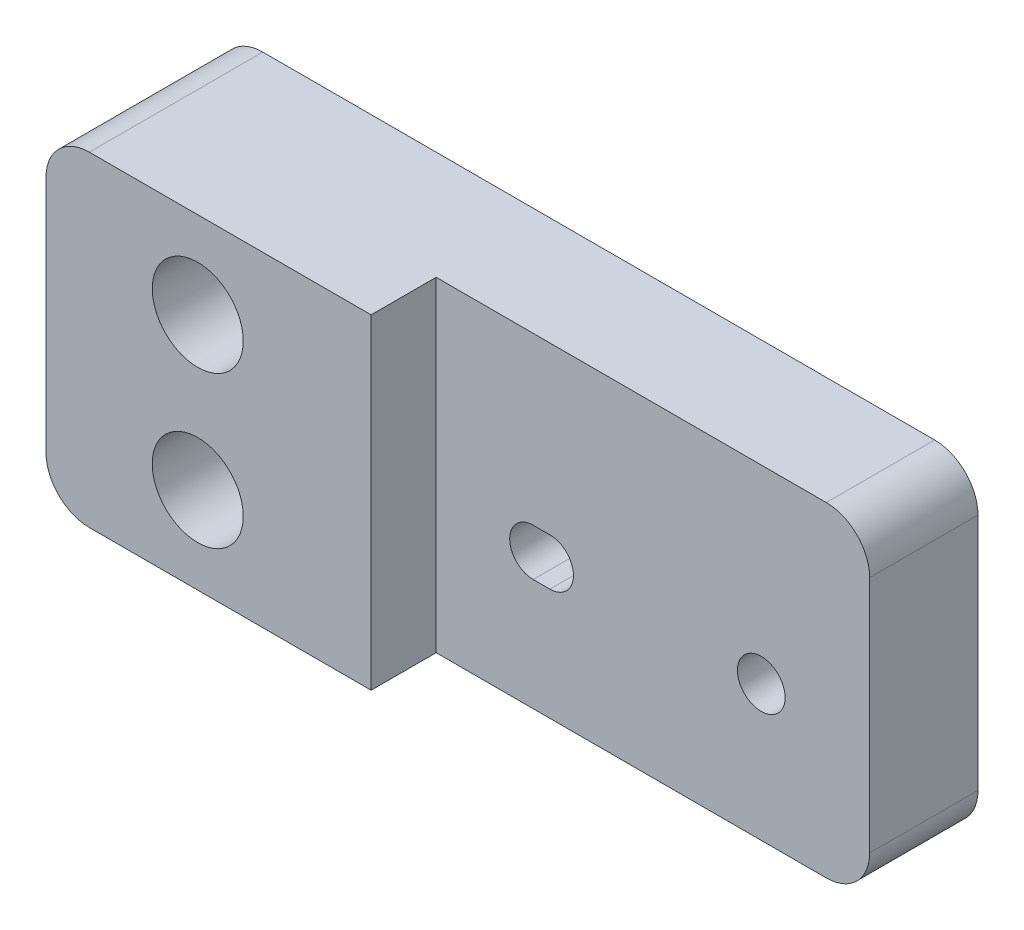
SolidWorks part; units mm, degrees
ref_plane "Plan de face" through (0, 0, 0) normal (0, 0, 1) x (1, 0, 0)
ref_plane "Plan de dessus" through (0, 0, 0) normal (0, 1, 0) x (1, 0, 0)
ref_plane "Plan de droite" through (0, 0, 0) normal (1, 0, 0) x (0, 0, -1)
sketch "Esquisse2" plane through (0, 0, 0) normal (0, 0, 1) x (1, 0, 0)
  line L0 (9.1879, 0.75) -> (5, 0.75) construction
  line L1 (18, 0.75) -> (-13, 0.75)
  line L2 (20, -1.25) -> (20, -12.25)
  line L3 (18, -14.25) -> (-13, -14.25)
  line L4 (-15, -1.25) -> (-15, -12.25)
  line L5 (20, -0.3) -> (20, -9.7) construction
  arc A0 (18, 0.75) -> (20, -1.25) centre (18, -1.25) cw
  arc A1 (20, -12.25) -> (18, -14.25) centre (18, -12.25) cw
  arc A2 (-13, 0.75) -> (-15, -1.25) centre (-13, -1.25) ccw
  arc A3 (-13, -14.25) -> (-15, -12.25) centre (-13, -12.25) cw
  circle A4 centre (-8, -10.25) radius 2.1
  circle A5 centre (-8, -3.25) radius 2.1
  point P12 (20, -14.25)
  point P15 (-15, 0.75)
  point P18 (-15, -14.25)
  dimension "D3" = 2
  dimension "D4" = 4.2
  dimension "D5" = 7
  dimension "D6" = 11
  dimension "D7" = 4.2
  dimension "D8" = 7
  dimension "D9" = 4
  dimension "D1" = 15
  dimension "D2" = 35
extrude "Boss.-Extru.1" add sketch "Esquisse2" along normal blind 5 contours A3 L3 A1 L2 A0 L1 A2 L4 | A4 | A5
sketch "Esquisse4" plane through (0, 0, 5) normal (0, 0, 1) x (1, 0, 0)
  line L0 (0, 0.75) -> (0, -14.25)
  line L4 (-15, -1.25) -> (-15, -12.25)
  line L5 (-13, -14.25) -> (18, -14.25)
  line L6 (20, -12.25) -> (20, -1.25)
  line L7 (18, 0.75) -> (-13, 0.75)
  line L8 (-15, -1.25) -> (-15, -12.25)
  line L9 (-13, -14.25) -> (0, -14.25)
  line L11 (0, 0.75) -> (-13, 0.75)
  circle A0 centre (-8, -10.25) radius 2.1 construction
  circle A1 centre (-8, -3.25) radius 2.1 construction
  circle A2 centre (-8, -10.25) radius 2.1
  circle A3 centre (-8, -3.25) radius 2.1
  arc A4 (-15, -12.25) -> (-13, -14.25) centre (-13, -12.25) ccw
  arc A5 (18, -14.25) -> (20, -12.25) centre (18, -12.25) ccw
  arc A6 (20, -1.25) -> (18, 0.75) centre (18, -1.25) ccw
  arc A7 (-13, 0.75) -> (-15, -1.25) centre (-13, -1.25) ccw
  arc A8 (-15, -12.25) -> (-13, -14.25) centre (-13, -12.25) ccw
  arc A11 (-13, 0.75) -> (-15, -1.25) centre (-13, -1.25) ccw
  dimension "D2" = 15
  dimension "D1" = 0
extrude "Boss.-Extru.2" add sketch "Esquisse4" along normal blind 3 contours L8 A8 L9 L0 L11 A11 | A3 | A2
sketch "Esquisse6" plane through (0, 0, 0) normal (0, 0, -1) x (-1, 0, 0)
  line L0 (-5.25, -8) -> (-4.4784, -8) construction
  line L1 (-5.25, -6.9148) -> (-4.4784, -6.9148)
  line L2 (-5.25, -9.0852) -> (-4.4784, -9.0852)
  circle A0 centre (-15, -7.9975) radius 1.1
  arc A1 (-5.25, -6.9148) -> (-5.25, -9.0852) centre (-5.25, -8) ccw
  arc A2 (-4.4784, -9.0852) -> (-4.4784, -6.9148) centre (-4.4784, -8) ccw
  point P4 (-4.8642, -8)
extrude "Enlèv. mat.-Extru.1" cut sketch "Esquisse6" against normal blind 10
